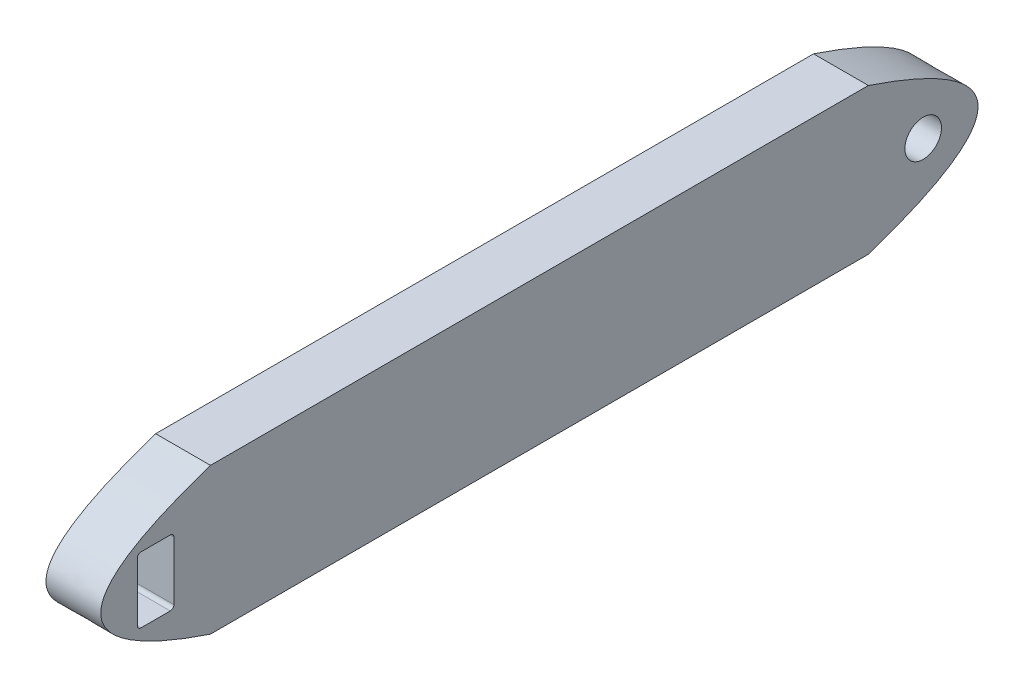
SolidWorks part; units mm, degrees
ref_plane "Front Plane" through (0, 0, 0) normal (0, 0, 1) x (1, 0, 0)
ref_plane "Top Plane" through (0, 0, 0) normal (0, 1, 0) x (1, 0, 0)
ref_plane "Right Plane" through (0, 0, 0) normal (1, 0, 0) x (0, 0, -1)
sketch "Sketch1" plane through (0, 0, 0) normal (1, 0, 0) x (0, 0, -1)
  line L0 (-42.1527, 21.9853) -> (137.8473, 21.9853)
  line L1 (-42.1527, -18.0147) -> (137.8473, -18.0147)
  circle A0 centre (-57.1527, 1.9853) radius 5
  circle A1 centre (152.8473, 1.9853) radius 5
  spline S0 degree 2 poles (137.8473, 21.9853) (197.8473, 1.9853) (137.8473, -18.0147) knots 0 0 0 1 1 1
  spline S1 degree 2 poles (-42.1527, 21.9853) (-102.1527, 1.9853) (-42.1527, -18.0147) knots 0 0 0 1 1 1
  point P10 (0, 0)
  point P11 (-44.1042, -19.5044)
  point P12 (0, 0)
  point P13 (0, 0)
  point P14 (0, 0)
  point P15 (0, 0)
  point P16 (0, 0)
  point P17 (0, 0)
  point P18 (0, 0)
  point P19 (0, 0)
  point P20 (0, 0)
  point P21 (0, 0)
  dimension "D8" = 10
  dimension "D1" = 180
  dimension "D2" = 40
  dimension "D3" = 20
  dimension "D4" = 30
  dimension "D5" = 30
  dimension "D6" = 15
  dimension "D7" = 15
extrude "Boss-Extrude1" add sketch "Sketch1" along normal blind 15
sketch "Sketch3" plane through (15, 0, 0) normal (1, 0, 0) x (0, 0, -1)
  line L0 (-57.1527, 9.6415) -> (-57.1527, -32.69) construction
  line L1 (-35.9244, 1.9853) -> (0.0786, 1.9853) construction
  line L2 (-53.1527, 10.9853) -> (-61.1527, 10.9853)
  line L3 (-62.1527, 9.9853) -> (-62.1527, -6.0147)
  line L4 (-52.1527, 9.9853) -> (-52.1527, -6.0147)
  line L5 (-53.1527, -7.0147) -> (-61.1527, -7.0147)
  arc A0 (-62.1527, 9.9853) -> (-61.1527, 10.9853) centre (-61.1527, 9.9853) cw
  arc A1 (-52.1527, 9.9853) -> (-53.1527, 10.9853) centre (-53.1527, 9.9853) ccw
  arc A2 (-52.1527, -6.0147) -> (-53.1527, -7.0147) centre (-53.1527, -6.0147) cw
  arc A3 (-62.1527, -6.0147) -> (-61.1527, -7.0147) centre (-61.1527, -6.0147) ccw
  circle A4 centre (-57.1527, 1.9853) radius 5 construction
  point P11 (-62.1527, 1.9853)
  point P12 (-57.1527, 10.9853)
  point P18 (-57.1527, -7.0147)
  point P19 (-52.1527, 1.9853)
  dimension "D1" = 1
  dimension "D2" = 18
  dimension "D3" = 10
  dimension "D4" = 5
  dimension "D5" = 9
extrude "Cut-Extrude1" cut sketch "Sketch3" against normal blind 15
